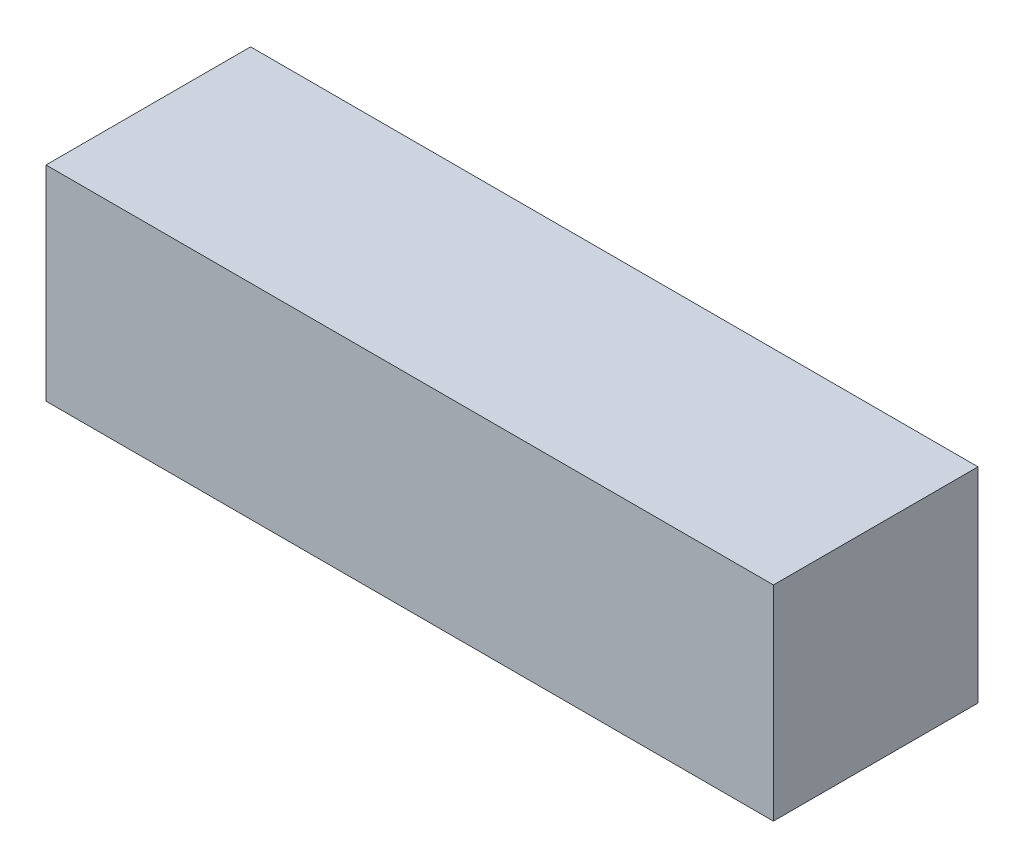
SolidWorks part; units mm, degrees
ref_plane "前视基准面" through (0, 0, 0) normal (0, 0, 1) x (1, 0, 0)
ref_plane "上视基准面" through (0, 0, 0) normal (0, 1, 0) x (1, 0, 0)
ref_plane "右视基准面" through (0, 0, 0) normal (1, 0, 0) x (0, 0, -1)
other "Configuration Table"
sketch "草图1" plane through (0, 0, 0) normal (0, 0, 1) x (1, 0, 0)
  line L1 (-80, -22.5) -> (80, -22.5)
  line L2 (-80, -22.5) -> (-80, 22.5)
  line L3 (-80, 22.5) -> (80, 22.5)
  line L4 (80, -22.5) -> (80, 22.5)
  line L5 (-80, -22.5) -> (80, 22.5) construction
  line L6 (-80, 22.5) -> (80, -22.5) construction
  point P0 (0, 0)
extrude "凸台-拉伸1" add sketch "草图1" along normal blind 45
